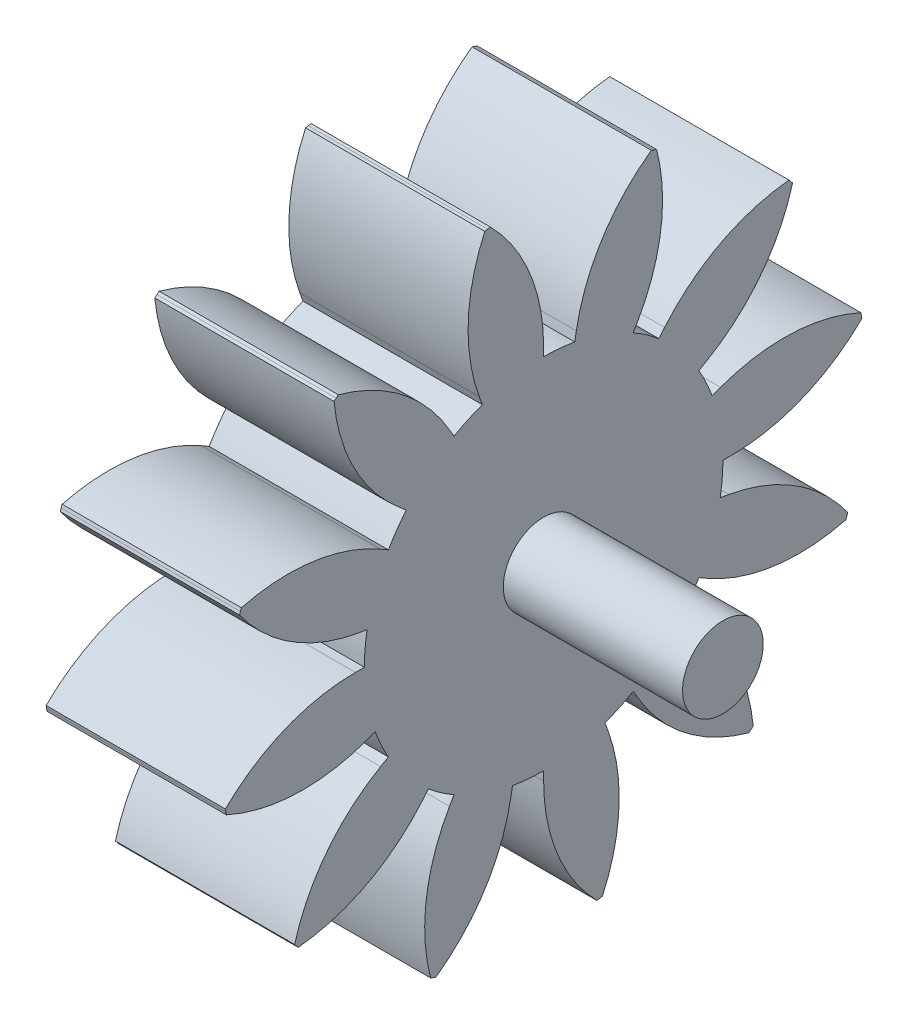
SolidWorks part; units mm, degrees
ref_plane "Front Plane" through (0, 0, 0) normal (0, 0, 1) x (1, 0, 0)
ref_plane "Top Plane" through (0, 0, 0) normal (0, 1, 0) x (1, 0, 0)
ref_plane "Right Plane" through (0, 0, 0) normal (1, 0, 0) x (0, 0, -1)
sketch "Sketch1" plane through (0, 0, 0) normal (1, 0, 0) x (0, 0, -1)
  line L0 (0, 0) -> (40, 0) construction
  line L1 (0, 0) -> (39.4514, 6.6019) construction
  line L2 (0, 0) -> (39.3923, 6.9459) construction
  line L3 (0, 0) -> (39.3302, 7.2894) construction
  line L4 (0, 0) -> (37.5877, 13.6808) construction
  line L5 (10, 0) -> (10.5, 0)
  line L6 (17.7531, 2.9709) -> (17.7265, 3.1257)
  line L7 (17.6986, 3.2802) -> (17.7265, 3.1257)
  line L8 (9.3969, 3.4202) -> (9.8668, 3.5912)
  line L9 (17.5387, -4.0491) -> (17.5733, -3.8959)
  line L10 (17.6067, -3.7424) -> (17.5733, -3.8959)
  line L11 (9.3969, -3.4202) -> (9.8668, -3.5912)
  line L12 (9.9619, -0.8716) -> (10.46, -0.9151)
  line L13 (15.0961, -9.8035) -> (15.181, -9.6714)
  line L14 (15.2649, -9.5385) -> (15.181, -9.6714)
  line L15 (7.6604, -6.4279) -> (8.0435, -6.7493)
  line L16 (9.0631, -4.2262) -> (9.5162, -4.4375)
  line L17 (10.8327, -14.3754) -> (10.9577, -14.2804)
  line L18 (11.0819, -14.1842) -> (10.9577, -14.2804)
  line L19 (5, -8.6603) -> (5.25, -9.0933)
  line L20 (7.0711, -7.0711) -> (7.4246, -7.4246)
  line L21 (5.2627, -17.2135) -> (5.4127, -17.1669)
  line L22 (5.5623, -17.119) -> (5.4127, -17.1669)
  line L23 (1.7365, -9.8481) -> (1.8233, -10.3405)
  line L24 (4.2262, -9.0631) -> (4.4375, -9.5162)
  line L25 (-0.942, -17.9753) -> (-0.7851, -17.9829)
  line L26 (-0.6282, -17.989) -> (-0.7851, -17.9829)
  line L27 (-1.7365, -9.8481) -> (-1.8233, -10.3405)
  line L28 (9.8481, -1.7365) -> (10.3405, -1.8233)
  line L29 (-7.0332, -16.5691) -> (-6.8883, -16.6298)
  line L30 (-6.7429, -16.6893) -> (-6.8883, -16.6298)
  line L31 (-5, -8.6603) -> (-5.25, -9.0933)
  line L32 (-2.5882, -9.6593) -> (-2.7176, -10.1422)
  line L33 (-12.276, -13.1644) -> (-12.1606, -13.271)
  line L34 (-12.0444, -13.3766) -> (-12.1606, -13.271)
  line L35 (8.6603, -5) -> (9.0933, -5.25)
  line L36 (-5.7358, -8.1915) -> (-6.0226, -8.6011)
  line L37 (-16.0381, -8.1718) -> (-15.9662, -8.3115)
  line L38 (-15.8931, -8.4505) -> (-15.9662, -8.3115)
  line L39 (16.8601, -6.3037) -> (16.9145, -6.1564)
  line L40 (16.9675, -6.0085) -> (16.9145, -6.1564)
  line L41 (-17.8658, -2.1936) -> (-17.846, -2.3495)
  line L42 (-17.8248, -2.5051) -> (-17.846, -2.3495)
  line L43 (7.6604, -6.4279) -> (8.0435, -6.7493)
  line L44 (5, -8.6603) -> (5.25, -9.0933)
  line L45 (-17.5387, 4.0491) -> (-17.5733, 3.8959)
  line L46 (-17.6067, 3.7424) -> (-17.5733, 3.8959)
  line L47 (11.4494, -13.8892) -> (11.5702, -13.7888)
  line L48 (-9.9619, 0.8716) -> (-10.46, 0.9151)
  line L49 (11.6901, -13.6873) -> (11.5702, -13.7888)
  line L50 (3.4202, -9.3969) -> (3.5912, -9.8668)
  line L51 (0, -10) -> (0, -10.5)
  line L52 (2.9709, -17.7531) -> (3.1257, -17.7265)
  line L53 (3.2802, -17.6986) -> (3.1257, -17.7265)
  line L54 (-1.7365, -9.8481) -> (-1.8233, -10.3405)
  line L55 (-5, 8.6603) -> (-5.25, 9.0933)
  line L56 (-5, -8.6603) -> (-5.25, -9.0933)
  line L57 (-5.2627, 17.2135) -> (-5.4127, 17.1669)
  line L58 (-5.5623, 17.119) -> (-5.4127, 17.1669)
  line L59 (-6.3037, -16.8601) -> (-6.1564, -16.9145)
  line L60 (-6.0085, -16.9675) -> (-6.1564, -16.9145)
  line L61 (0.942, 17.9753) -> (0.7851, 17.9829)
  line L62 (0.6282, 17.989) -> (0.7851, 17.9829)
  line L63 (-6.4279, -7.6604) -> (-6.7493, -8.0435)
  line L64 (-8.6603, -5) -> (-9.0933, -5.25)
  line L65 (7.0332, 16.5691) -> (6.8883, 16.6298)
  line L66 (6.7429, 16.6893) -> (6.8883, 16.6298)
  line L67 (5, 8.6603) -> (5.25, 9.0933)
  line L68 (-13.8892, -11.4494) -> (-13.7888, -11.5702)
  line L69 (12.276, 13.1644) -> (12.1606, 13.271)
  line L70 (12.0444, 13.3766) -> (12.1606, 13.271)
  line L71 (7.6604, 6.4279) -> (8.0435, 6.7493)
  line L72 (5.7358, 8.1915) -> (6.0226, 8.6011)
  line L73 (16.0381, 8.1718) -> (15.9662, 8.3115)
  line L74 (15.8931, 8.4505) -> (15.9662, 8.3115)
  line L75 (9.3969, 3.4202) -> (9.8668, 3.5912)
  line L76 (8.1915, 5.7358) -> (8.6011, 6.0226)
  line L77 (-13.6873, -11.6901) -> (-13.7888, -11.5702)
  line L78 (-9.3969, -3.4202) -> (-9.8668, -3.5912)
  line L79 (-10, 0) -> (-10.5, 0)
  line L80 (-17.7531, -2.9709) -> (-17.7265, -3.1257)
  line L81 (-17.6986, -3.2802) -> (-17.7265, -3.1257)
  line L82 (-9.8481, 1.7365) -> (-10.3405, 1.8233)
  line L83 (-8.6603, 5) -> (-9.0933, 5.25)
  line L84 (-16.8601, 6.3037) -> (-16.9145, 6.1564)
  line L85 (-16.9675, 6.0085) -> (-16.9145, 6.1564)
  line L86 (-7.6604, 6.4279) -> (-8.0435, 6.7493)
  line L87 (-5, 8.6603) -> (-5.25, 9.0933)
  line L88 (-11.4494, 13.8892) -> (-11.5702, 13.7888)
  line L89 (-11.6901, 13.6873) -> (-11.5702, 13.7888)
  line L90 (-3.4202, 9.3969) -> (-3.5912, 9.8668)
  line L91 (0, 10) -> (0, 10.5)
  line L92 (-2.9709, 17.7531) -> (-3.1257, 17.7265)
  line L93 (-3.2802, 17.6986) -> (-3.1257, 17.7265)
  line L94 (1.7365, 9.8481) -> (1.8233, 10.3405)
  line L95 (5, 8.6603) -> (5.25, 9.0933)
  line L96 (6.3037, 16.8601) -> (6.1564, 16.9145)
  line L97 (6.0085, 16.9675) -> (6.1564, 16.9145)
  line L98 (6.4279, 7.6604) -> (6.7493, 8.0435)
  line L99 (8.6603, 5) -> (9.0933, 5.25)
  line L100 (13.8892, 11.4494) -> (13.7888, 11.5702)
  line L101 (13.6873, 11.6901) -> (13.7888, 11.5702)
  circle A0 centre (0, 0) radius 2.25
  circle A1 centre (0, 0) radius 10
  circle A2 centre (0, 0) radius 18 construction
  arc A3 (10.5, 0) -> (17.7531, 2.9709) centre (10.5, 10.3394) ccw
  arc A4 (9.8668, 3.5912) -> (17.6986, 3.2802) centre (13.4031, -6.1247) cw
  arc A5 (10.3405, -1.8233) -> (16.9675, -6.0085) centre (8.5451, -12.0057) cw
  arc A6 (9.0933, -5.25) -> (16.8601, -6.3037) centre (14.263, 3.7042) ccw
  arc A7 (8.0435, -6.7493) -> (11.6901, -13.6873) centre (1.3974, -14.6697) cw
  arc A8 (5.25, -9.0933) -> (11.4494, -13.8892) centre (14.2042, -3.9235) ccw
  arc A9 (3.5912, -9.8668) -> (3.2802, -17.6986) centre (-6.1247, -13.4031) cw
  arc A10 (0, -10.5) -> (2.9709, -17.7531) centre (10.3394, -10.5) ccw
  arc A11 (-1.8233, -10.3405) -> (-6.0085, -16.9675) centre (-12.0057, -8.5451) cw
  arc A12 (-5.25, -9.0933) -> (-6.3037, -16.8601) centre (3.7042, -14.263) ccw
  arc A13 (-6.7493, -8.0435) -> (-13.6873, -11.6901) centre (-14.6697, -1.3974) cw
  arc A14 (-9.0933, -5.25) -> (-13.8892, -11.4494) centre (-3.9235, -14.2042) ccw
  arc A15 (-9.8668, -3.5912) -> (-17.6986, -3.2802) centre (-13.4031, 6.1247) cw
  arc A16 (-10.5, 0) -> (-17.7531, -2.9709) centre (-10.5, -10.3394) ccw
  arc A17 (-10.3405, 1.8233) -> (-16.9675, 6.0085) centre (-8.5451, 12.0057) cw
  arc A18 (-9.0933, 5.25) -> (-16.8601, 6.3037) centre (-14.263, -3.7042) ccw
  arc A19 (-8.0435, 6.7493) -> (-11.6901, 13.6873) centre (-1.3974, 14.6697) cw
  arc A20 (-5.25, 9.0933) -> (-11.4494, 13.8892) centre (-14.2042, 3.9235) ccw
  arc A21 (-3.5912, 9.8668) -> (-3.2802, 17.6986) centre (6.1247, 13.4031) cw
  arc A22 (0, 10.5) -> (-2.9709, 17.7531) centre (-10.3394, 10.5) ccw
  arc A23 (1.8233, 10.3405) -> (6.0085, 16.9675) centre (12.0057, 8.5451) cw
  arc A24 (5.25, 9.0933) -> (6.3037, 16.8601) centre (-3.7042, 14.263) ccw
  arc A25 (6.7493, 8.0435) -> (13.6873, 11.6901) centre (14.6697, 1.3974) cw
  arc A26 (9.0933, 5.25) -> (13.8892, 11.4494) centre (3.9235, 14.2042) ccw
  point P10 (16.9145, 6.1564)
  point P11 (17.6986, 3.2802)
  point P12 (17.7265, 3.1257)
  point P13 (17.7531, 2.9709)
  point P14 (10, 0)
  point P19 (17.7398, 3.0483)
  point P20 (17.7126, 3.203)
  point P182 (0, 0)
  point P211 (0, 0)
  dimension "D3" = 20
  dimension "D4" = 10
  dimension "D5" = 10.5
  dimension "D6" = 9.5
  dimension "D7" = 40
  dimension "D8" = 8
  dimension "D9" = 0.5
  dimension "D1" = 12
extrude "Boss-Extrude2" add sketch "Sketch1" along normal blind 10
sketch "Sketch2" plane through (10, 0, 0) normal (1, 0, 0) x (0, 0, -1)
  circle A0 centre (0, 0) radius 2.25
  circle A1 centre (0, 0) radius 2.25 construction
extrude "Boss-Extrude3" add sketch "Sketch2" along normal blind 10 separate body
sketch "Sketch5" plane through (20, 0, 0) normal (1, 0, 0) x (0, 0, -1)
  line L0 (39.25, 7.5) -> (39.25, 8) construction
  line L1 (-2.75, 8) -> (47.25, 8)
  line L2 (-2.75, 8) -> (-2.75, -8)
  line L3 (-2.75, -8) -> (47.25, -8)
  line L4 (47.25, 8) -> (47.25, -8)
  line L5 (-2.25, 0) -> (-2.75, 0) construction
  line L7 (46.75, 0) -> (47.25, 0) construction
  line L8 (39.25, -7.5) -> (39.25, -8) construction
  circle A0 centre (0, 0) radius 2.25 construction
  circle A1 centre (0, 0) radius 2.25 construction
  circle A2 centre (39.25, 0) radius 7.5
  dimension "D2" = 15
  dimension "D1" = 50
  dimension "D3" = 16
equation "\"Gear_angle\" = 20"
equation "\"D3@Sketch1\"=\"Gear_angle\""
equation "\"D4@Sketch1\"=\"Gear_angle\"*0.5"
equation "\"D5@Sketch1\"=\"Gear_angle\"*0.5 +0.5"
equation "\"D6@Sketch1\"=\"Gear_angle\"*0.5 -0.5"
equation "\"Gear_diameter\" = 20mm"
equation "\"Gear_tooth_height\"= 2mm"
equation "\"gear_thickeness\"=10"
